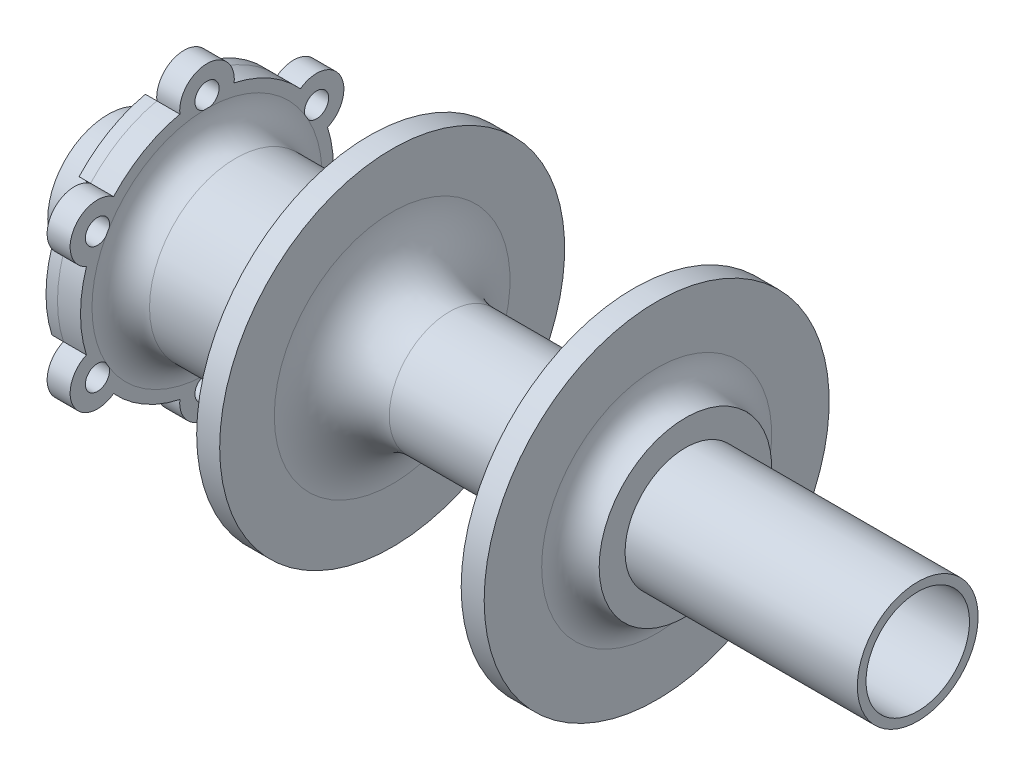
SolidWorks part; units mm, degrees
material "6061 Alloy"
ref_plane "Front Plane" through (0, 0, 0) normal (0, 0, 1) x (1, 0, 0)
ref_plane "Top Plane" through (0, 0, 0) normal (0, 1, 0) x (1, 0, 0)
ref_plane "Right Plane" through (0, 0, 0) normal (1, 0, 0) x (0, 0, -1)
sketch "Sketch1" plane through (0, 0, 0) normal (0, 0, 1) x (1, 0, 0)
  line L0 (0, 30) -> (0, 20)
  line L1 (0, 30) -> (4, 30)
  line L2 (4, 30) -> (4, 20.5)
  line L3 (14, 10.5) -> (36, 10.5)
  line L4 (46, 20.5) -> (46, 30)
  line L5 (46, 30) -> (50, 30)
  line L6 (50, 30) -> (50, 20)
  line L7 (95.4, 9) -> (81.4, 9)
  line L8 (0, 0) -> (0, 6.4) construction
  line L9 (0, 0) -> (134.3966, 0) construction
  line L10 (-5, 15) -> (-23.2, 15)
  line L11 (-28.2, 20) -> (-28.2, 26.875)
  line L12 (-28.2, 26.875) -> (-32.2, 26.875)
  line L13 (-32.2, 26.875) -> (-32.2, 10.5)
  line L14 (-32.2, 10.5) -> (-45.4, 10.5)
  line L15 (-45.4, 10.5) -> (-45.4, 9)
  line L16 (-45.4, 9) -> (-31.4, 9)
  line L17 (0, 15) -> (0, 59.4663) construction
  line L18 (55, 10.5) -> (95.4, 10.5)
  line L19 (95.4, 10.5) -> (95.4, 9)
  line L21 (25, 10.5) -> (25, 50.7885) construction
  line L22 (-31.4, 9) -> (-31.4, 6.4)
  line L23 (-31.4, 6.4) -> (81.4, 6.4)
  line L24 (81.4, 6.4) -> (81.4, 9)
  line L25 (55, 10.5) -> (55, 15)
  arc A0 (36, 10.5) -> (46, 20.5) centre (36, 20.5) ccw
  arc A1 (14, 10.5) -> (4, 20.5) centre (14, 20.5) cw
  arc A3 (-23.2, 15) -> (-28.2, 20) centre (-23.2, 20) cw
  arc A4 (-5, 15) -> (0, 20) centre (-5, 20) ccw
  arc A6 (50, 20) -> (55, 15) centre (55, 20) ccw
  dimension "D6" = 10
  dimension "D7" = 5
  dimension "D13" = 5
  dimension "D1" = 50
  dimension "D2" = 4
  dimension "D3" = 10.5
  dimension "D4" = 45.4
  dimension "D5" = 30
  dimension "D8" = 26.875
  dimension "D9" = 4
  dimension "D10" = 14
  dimension "D11" = 28.2
  dimension "D12" = 45.4
  dimension "D14" = 15
  dimension "D15" = 40.4
  dimension "D16" = 14
  dimension "D17" = 6.4
  dimension "D18" = 9
  dimension "D19" = 15
revolve "Revolve1" add sketch "Sketch1" angle 360 about L9
sketch "Sketch2" plane through (-32.2, 0, 0) normal (-1, 0, 0) x (0, 0, 1)
  line L0 (0, 0) -> (4.7222, 21.4872) construction
  line L1 (0, 0) -> (20.9696, 6.654) construction
  arc A0 (-4.7222, 21.4872) -> (-16.2474, 14.8332) centre (0, 0) ccw
  circle A1 centre (0, 22) radius 2.5 construction
  circle A2 centre (0, 22) radius 4.75 construction
  arc A3 (-4.7222, 21.4872) -> (4.7222, 21.4872) centre (0, 22) cw
  circle A4 centre (0, 0) radius 27.5
  arc A5 (16.2474, 14.8332) -> (20.9696, 6.654) centre (19.0526, 11) cw
  arc A6 (20.9696, -6.654) -> (16.2474, -14.8332) centre (19.0526, -11) cw
  arc A7 (4.7222, -21.4872) -> (-4.7222, -21.4872) centre (0, -22) cw
  arc A8 (-16.2474, -14.8332) -> (-20.9696, -6.654) centre (-19.0526, -11) cw
  arc A9 (-20.9696, 6.654) -> (-16.2474, 14.8332) centre (-19.0526, 11) cw
  arc A10 (-20.9696, 6.654) -> (-20.9696, -6.654) centre (0, 0) ccw
  arc A11 (-16.2474, -14.8332) -> (-4.7222, -21.4872) centre (0, 0) ccw
  arc A12 (4.7222, -21.4872) -> (16.2474, -14.8332) centre (0, 0) ccw
  arc A13 (20.9696, -6.654) -> (20.9696, 6.654) centre (0, 0) ccw
  arc A14 (16.2474, 14.8332) -> (4.7222, 21.4872) centre (0, 0) ccw
  point P6 (-4.7222, 21.4872)
  point P7 (4.7222, 21.4872)
  point P9 (0, 22)
  point P10 (19.0526, 11)
  point P30 (19.0526, -11)
  point P31 (0, -22)
  point P32 (-19.0526, -11)
  point P33 (-19.0526, 11)
  dimension "D1" = 44
  dimension "D2" = 5
  dimension "D3" = 9.5
  dimension "D4" = 55
  dimension "D6" = 60
  dimension "D5" = 6
extrude "Cut-Extrude1" cut sketch "Sketch2" against normal up to next
sketch "Sketch3" plane through (-32.2, 0, 0) normal (-1, 0, 0) x (0, 0, 1)
  point P0 (-19.0526, 11)
  point P3 (0, 22)
  point P6 (19.0526, 11)
  point P9 (19.0526, -11)
  point P12 (0, -22)
  point P15 (-19.0526, -11)
hole_wizard "M5x0.8 Tapped Hole1" positions "Sketch3" profile "Sketch4" tap size "M5x0.8" standard "ANSI Metric"
sketch "Sketch4" plane through (-32.2, 11, -19.0526) normal (0, 1, 0) x (0, 0, 1)
  line L0 (0, 0) -> (0, 4)
  line L1 (0, 4) -> (2.1, 4)
  line L2 (2.1, 4) -> (2.1, 0)
  line L5 (2.1, 0) -> (0, 0)
  line L11 (0, -6.35) -> (0, 107.95) construction
  dimension "Thru Tap Drill Dia." = 4.2
  dimension "Thru Tap Drill Depth" = 4
sketch "Sketch5" plane through (-32.2, 0, 0) normal (-1, 0, 0) x (0, 0, 1)
  line L0 (0, 0) -> (4.7222, 21.4872) construction
  line L1 (0, 0) -> (20.9696, 6.654) construction
  arc A0 (-4.7222, 21.4872) -> (-16.2474, 14.8332) centre (0, 0) ccw
  arc A1 (16.2474, 14.8332) -> (4.7222, 21.4872) centre (0, 0) ccw construction
  circle A2 centre (0, 22) radius 4.75 construction
  arc A3 (4.7222, 21.4872) -> (-4.7222, 21.4872) centre (0, 22) ccw construction
  arc A4 (-4.7222, 21.4872) -> (4.7222, 21.4872) centre (0, 22) ccw
  arc A5 (16.2474, 14.8332) -> (20.9696, 6.654) centre (19.0526, 11) ccw
  arc A6 (20.9696, -6.654) -> (16.2474, -14.8332) centre (19.0526, -11) ccw
  arc A7 (4.7222, -21.4872) -> (-4.7222, -21.4872) centre (0, -22) ccw
  arc A8 (-16.2474, -14.8332) -> (-20.9696, -6.654) centre (-19.0526, -11) ccw
  arc A9 (-20.9696, 6.654) -> (-16.2474, 14.8332) centre (-19.0526, 11) ccw
  arc A10 (-20.9696, 6.654) -> (-20.9696, -6.654) centre (0, 0) ccw
  arc A11 (20.9696, -6.654) -> (20.9696, 6.654) centre (0, 0) ccw
  arc A12 (4.7222, -21.4872) -> (16.2474, -14.8332) centre (0, 0) ccw
  arc A13 (-16.2474, -14.8332) -> (-4.7222, -21.4872) centre (0, 0) ccw
  arc A14 (16.2474, 14.8332) -> (4.7222, 21.4872) centre (0, 0) ccw
  circle A15 centre (0, 0) radius 10.5
  circle A16 centre (0, 0) radius 10.5 construction
  dimension "D2" = 60
  dimension "D1" = 6
extrude "Boss-Extrude1" add sketch "Sketch5" along normal blind 2
sketch "Sketch6" plane through (0, 0, 0) normal (0, 0, 1) x (1, 0, 0)
  line L0 (-32.2, 30) -> (-32.2, -30)
  line L1 (-32.2, 14.8332) -> (-32.2, 6.25) construction
  line L2 (-32.2, -6.25) -> (-32.2, -14.8332) construction
  line L3 (-32.2, 30) -> (-28.2, 30)
  line L4 (-28.2, 30) -> (-28.2, -30)
  line L5 (-28.2, -30) -> (-32.2, -30)
  line L6 (-28.2, -6.654) -> (-28.2, 6.654) construction
  dimension "D1" = 30
  dimension "D2" = 60
split line "Split Line1"
fillet "Fillet1" radius 5 1 edges at (-34.2, 0, 10.5)
